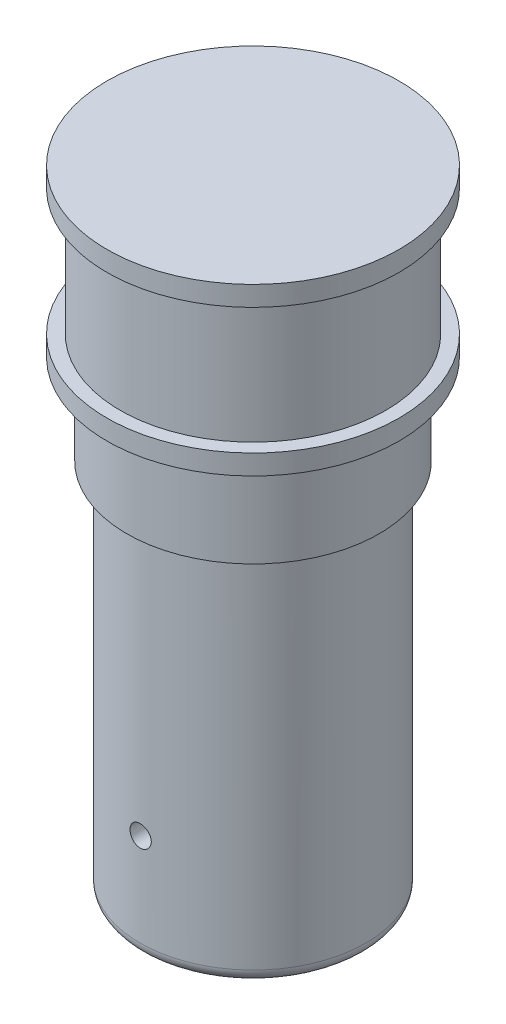
SolidWorks part; units mm, degrees
material "ABS"
ref_plane "Front Plane" through (0, 0, 0) normal (0, 0, 1) x (1, 0, 0)
ref_plane "Top Plane" through (0, 0, 0) normal (0, 1, 0) x (1, 0, 0)
ref_plane "Right Plane" through (0, 0, 0) normal (1, 0, 0) x (0, 0, -1)
sketch "Sketch1" plane through (0, 0, 0) normal (0, 0, 1) x (1, 0, 0)
  line L2 (-8.5, -35) -> (-8.5, -6.8)
  line L3 (-9.5, 0) -> (-11, 0)
  line L4 (-11, 0) -> (-11, 1.5)
  line L5 (-11, 1.5) -> (-10, 1.5)
  line L6 (-10, 1.5) -> (-10, 11)
  line L7 (-10, 11) -> (-11, 11)
  line L8 (-11, 11) -> (-11, 12.5)
  line L9 (-11, 12.5) -> (0, 12.5)
  line L10 (0, 12.5) -> (0, -21)
  line L11 (-4, -35) -> (-8.5, -35)
  line L12 (-4, -21) -> (-4, -35)
  line L13 (0, -21) -> (-4, -21)
  line L14 (-8.5, -6.8) -> (-9.5, -6.8)
  line L15 (-9.5, -6.8) -> (-9.5, 0)
  point P1 (0, -1.9049)
  point P14 (-2.3337, -2.0559)
  point P15 (-4, -5.3293)
  dimension "D1" = 8.5
  dimension "D2" = 1
  dimension "D3" = 35
  dimension "D4" = 1.5
  dimension "D5" = 4
  dimension "D6" = 14
  dimension "D7" = 12.5
  dimension "D8" = 10
  dimension "D9" = 28.2
  dimension "D10" = 1
revolve "Revolve1" add sketch "Sketch1" angle 360 about L10
fillet "Fillet1" radius 1 2 edges at (-8.5, -35, 0) (-4, -35, 0)
hole_wizard "M2x0.4 Tapped Hole1" positions "Sketch2" profile "Sketch3" tap size "M2x0.4" standard "ANSI Metric"
sketch "Sketch2" plane through (0, 0, 0) normal (0, 0, 1) x (1, 0, 0)
  line L0 (-7.5, -35) -> (7.5, -35) construction
  point P0 (0, -27)
  dimension "D1" = 8
sketch "Sketch3" plane through (0, -27, 0) normal (1, 0, 0) x (0, 1, 0)
  line L0 (0, 0) -> (0, 8.5)
  line L1 (0, 8.5) -> (0.8, 8.5)
  line L2 (0.8, 8.5) -> (0.8, 0)
  line L5 (0.8, 0) -> (0, 0)
  line L11 (0, -6.35) -> (0, 107.95) construction
  dimension "Thru Tap Drill Dia." = 1.6
  dimension "Thru Tap Drill Depth" = 8.5
cosmetic thread "Hole Thread1" parameters "D2"=2
